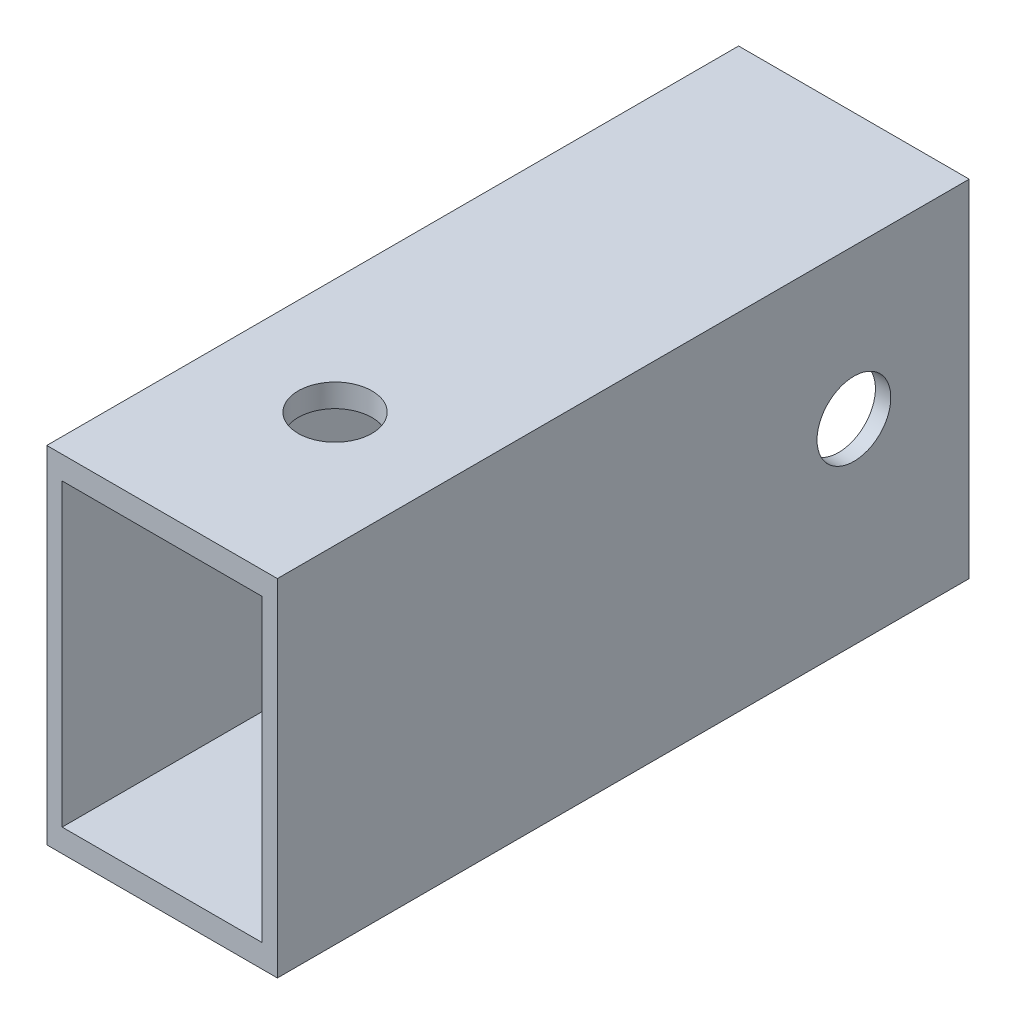
SolidWorks part; units mm, degrees
ref_plane "正面" through (0, 0, 0) normal (0, 0, 1) x (1, 0, 0)
ref_plane "平面" through (0, 0, 0) normal (0, 1, 0) x (1, 0, 0)
ref_plane "右側面" through (0, 0, 0) normal (1, 0, 0) x (0, 0, -1)
sketch "ｽｹｯﾁ1" plane through (0, 0, 0) normal (0, 0, 1) x (1, 0, 0)
  line L1 (-5, -7.5) -> (5, -7.5)
  line L2 (-5, -7.5) -> (-5, 7.5)
  line L3 (-5, 7.5) -> (5, 7.5)
  line L4 (5, -7.5) -> (5, 7.5)
  line L5 (-5, -7.5) -> (5, 7.5) construction
  line L6 (-5, 7.5) -> (5, -7.5) construction
  line L7 (-4.3333, -6.5) -> (4.3333, -6.5)
  line L8 (-4.3333, -6.5) -> (-4.3333, 6.5)
  line L9 (-4.3333, 6.5) -> (4.3333, 6.5)
  line L10 (4.3333, -6.5) -> (4.3333, 6.5)
  line L11 (-4.3333, -6.5) -> (4.3333, 6.5) construction
  line L12 (-4.3333, 6.5) -> (4.3333, -6.5) construction
  point P0 (0, 0)
  point P6 (0, 0)
  dimension "D1" = 1
  dimension "D2" = 10
  dimension "D3" = 15
extrude "ﾎﾞｽ - 押し出し1" add sketch "ｽｹｯﾁ1" along normal blind 30
sketch "ｽｹｯﾁ3" plane through (0, 7.5, 0) normal (0, 1, 0) x (1, 0, 0)
  line L0 (5, -30) -> (-5, -30) construction
  line L1 (-5, -30) -> (-5, 0) construction
  circle A0 centre (0, -22.5) radius 1.6
  dimension "D1" = 3.2
  dimension "D2" = 7.5
  dimension "D3" = 5
extrude "ｶｯﾄ - 押し出し2" cut sketch "ｽｹｯﾁ3" against normal through all
sketch "ｽｹｯﾁ4" plane through (-5, 0, 0) normal (-1, 0, 0) x (0, 0, 1)
  line L1 (30, 7.5) -> (0, 7.5) construction
  line L2 (0, 7.5) -> (0, -7.5) construction
  circle A0 centre (5, 1) radius 1.6
  dimension "D1" = 3.2
  dimension "D2" = 5
  dimension "D3" = 6.5
extrude "ｶｯﾄ - 押し出し3" cut sketch "ｽｹｯﾁ4" against normal through all
